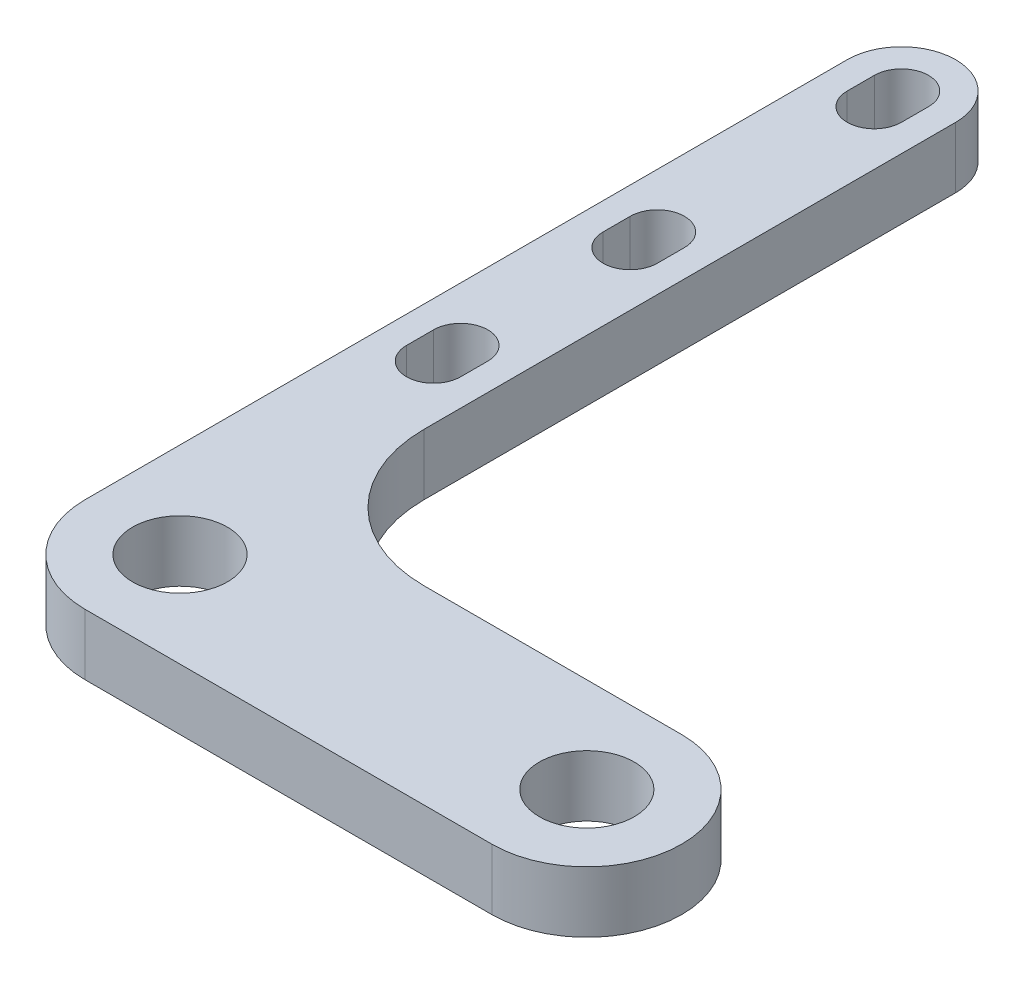
SolidWorks part; units mm, degrees
ref_plane "Front Plane" through (0, 0, 0) normal (0, 0, 1) x (1, 0, 0)
ref_plane "Top Plane" through (0, 0, 0) normal (0, 1, 0) x (1, 0, 0)
ref_plane "Right Plane" through (0, 0, 0) normal (1, 0, 0) x (0, 0, -1)
sketch "Sketch1" plane through (0, 0, 0) normal (0, 1, 0) x (1, 0, 0)
  line L0 (0, 0) -> (30, 0) construction
  line L1 (11, 7) -> (30, 7)
  line L2 (0, -7) -> (30, -7)
  line L3 (-3, 21.7) -> (-3, 23.7) construction
  line L4 (-5, 21.7) -> (-5, 23.7)
  line L5 (-1, 21.7) -> (-1, 23.7)
  line L6 (-3, 36.2) -> (-3, 38.2) construction
  line L7 (-5, 36.2) -> (-5, 38.2)
  line L8 (-1, 36.2) -> (-1, 38.2)
  line L9 (-3, 54.2) -> (-3, 56.2) construction
  line L10 (-5, 54.2) -> (-5, 56.2)
  line L11 (-1, 54.2) -> (-1, 56.2)
  line L12 (-3, 56.2) -> (-3, 21.7) construction
  line L13 (1, 56.2) -> (1, 17)
  line L14 (-7, 56.2) -> (-7, 21.7)
  line L15 (-7, 0) -> (-7, 21.7)
  circle A0 centre (0, 0) radius 3.5
  circle A1 centre (30, 0) radius 3.5
  arc A4 (-7, 0) -> (0, -7) centre (0, 0) ccw
  arc A5 (30, -7) -> (30, 7) centre (30, 0) ccw
  arc A6 (-5, 21.7) -> (-1, 21.7) centre (-3, 21.7) ccw
  arc A7 (-1, 23.7) -> (-5, 23.7) centre (-3, 23.7) ccw
  arc A8 (-5, 36.2) -> (-1, 36.2) centre (-3, 36.2) ccw
  arc A9 (-1, 38.2) -> (-5, 38.2) centre (-3, 38.2) ccw
  arc A10 (-5, 54.2) -> (-1, 54.2) centre (-3, 54.2) ccw
  arc A11 (-1, 56.2) -> (-5, 56.2) centre (-3, 56.2) ccw
  arc A12 (1, 56.2) -> (-7, 56.2) centre (-3, 56.2) ccw
  arc A14 (1, 17) -> (11, 7) centre (11, 17) ccw
  point P7 (-3, 22.7)
  point P9 (30, 0)
  point P17 (-3, 37.2)
  point P24 (-3, 55.2)
  point P31 (-8.7, 38.95)
  dimension "D1" = 18
  dimension "D2" = 7
  dimension "D4" = 7
  dimension "D7" = 2
  dimension "D11" = 4
  dimension "D12" = 20
  dimension "D3" = 30
  dimension "D5" = 22.7
  dimension "D6" = 14.5
  dimension "D8" = 2
  dimension "D9" = 2
  dimension "D10" = 2
extrude "Boss-Extrude1" add sketch "Sketch1" along normal blind 4.5
